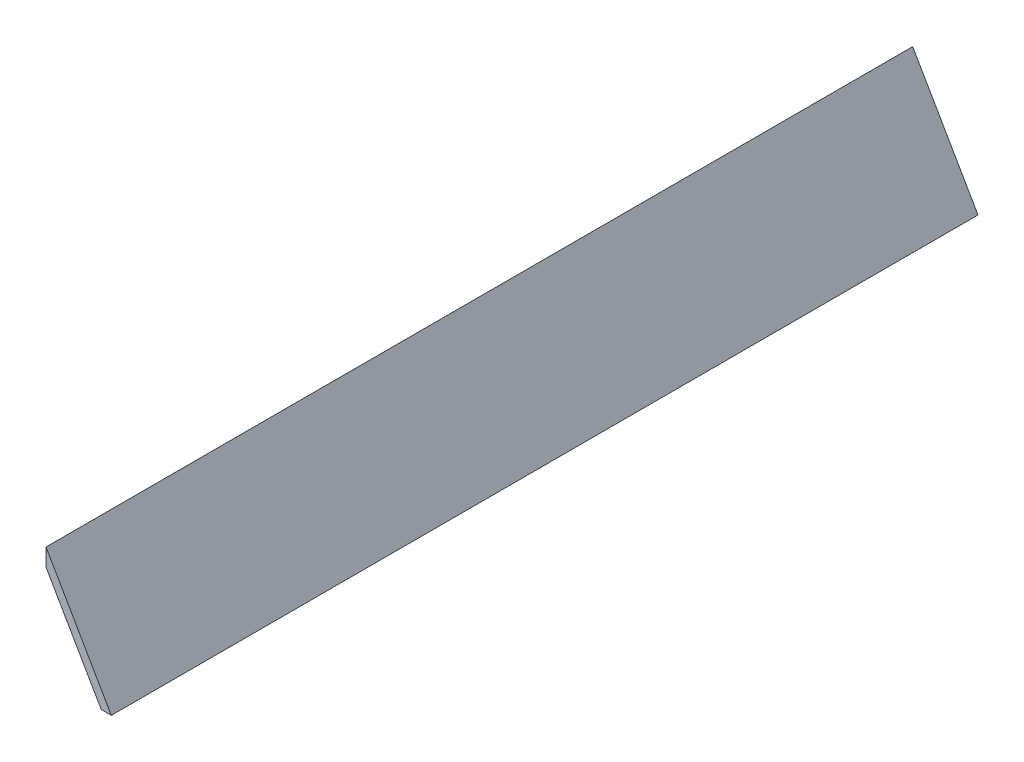
SolidWorks part; units mm, degrees
ref_plane "Alzado" through (0, 0, 0) normal (0, 0, 1) x (1, 0, 0)
ref_plane "Planta" through (0, 0, 0) normal (0, 1, 0) x (1, 0, 0)
ref_plane "Vista lateral" through (0, 0, 0) normal (1, 0, 0) x (0, 0, -1)
sketch "Croquis2" plane through (0, 0, 0) normal (0, 0, 1) x (1, 0, 0)
  line L11 (-2, 95.9989) -> (-2, 97.9989)
  line L12 (-2, 97.9989) -> (5.4971, 85.0068)
  line L15 (-2, 95.9989) -> (4.3416, 85.0068)
  line L16 (4.3416, 85.0068) -> (5.4971, 85.0068)
  dimension "D1" = 4.3416
  dimension "D2" = 5.4971
  dimension "D3" = 2
  dimension "D4" = 85.0068
  dimension "D5" = 95.9989
  dimension "D6" = 97.9989
extrude "Saliente-Extruir2" add sketch "Croquis2" against normal blind 99.5
